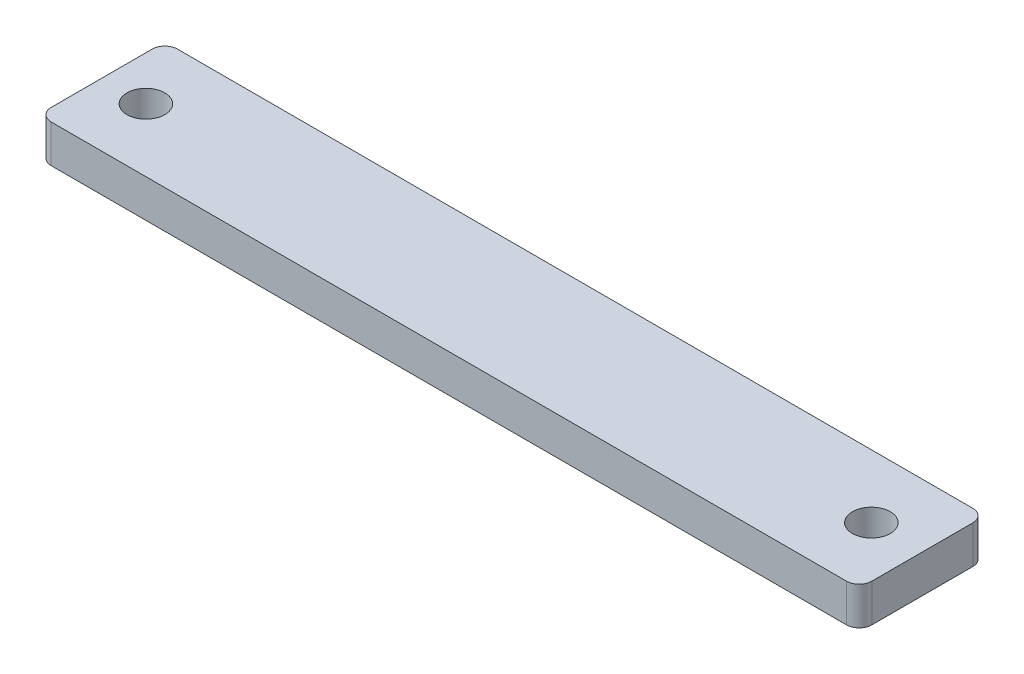
SolidWorks part; units mm, degrees
ref_plane "Alzado" through (0, 0, 0) normal (0, 0, 1) x (1, 0, 0)
ref_plane "Planta" through (0, 0, 0) normal (0, 1, 0) x (1, 0, 0)
ref_plane "Vista lateral" through (0, 0, 0) normal (1, 0, 0) x (0, 0, -1)
sketch "Croquis1" plane through (0, 0, 0) normal (0, 1, 0) x (1, 0, 0)
  line L0 (-32.2324, 6.0704) -> (32.7676, 6.0704)
  line L1 (-32.2324, 6.0704) -> (-32.2324, -3.9296)
  line L2 (-32.2324, -3.9296) -> (32.7676, -3.9296)
  line L3 (32.7676, 6.0704) -> (32.7676, -3.9296)
  line L4 (0, 0) -> (0, 3.0101) construction
  circle A0 centre (-28.7324, 1.0704) radius 1.5
  circle A2 centre (28.7324, 1.0704) radius 1.5
  dimension "D3" = 3
  dimension "D4" = 3.5
  dimension "D1" = 65
  dimension "D2" = 10
extrude "Saliente-Extruir1" add sketch "Croquis1" along normal blind 3
fillet "Redondeo1" radius 1 4 edges at (-32.2324, 1.5, -6.0704) (32.7676, 1.5, -6.0704) (32.7676, 1.5, 3.9296) (-32.2324, 1.5, 3.9296)
